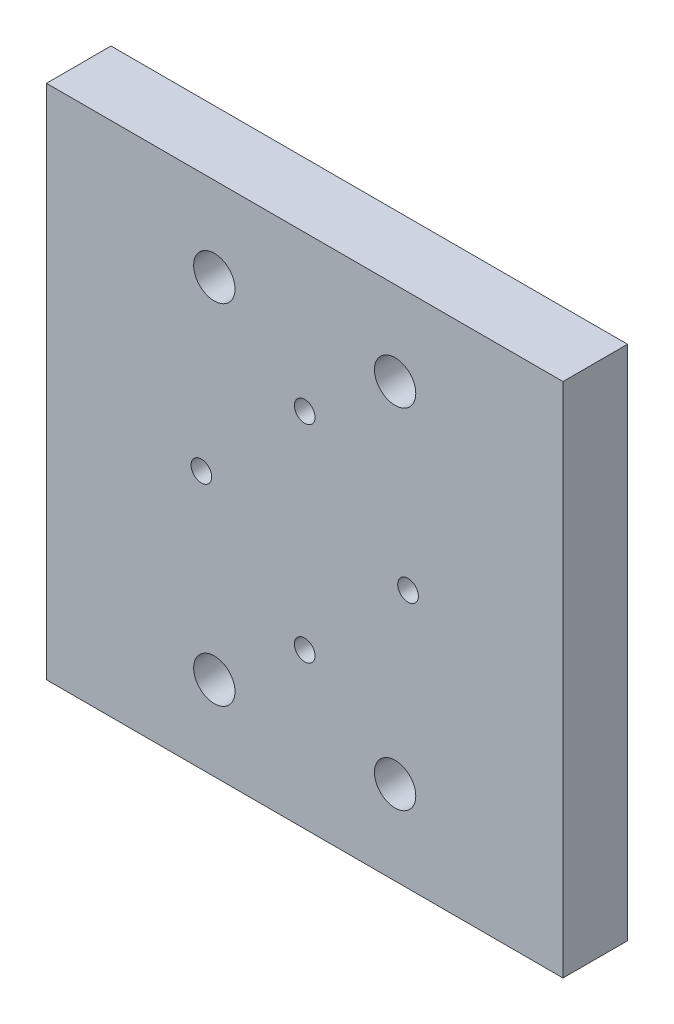
SolidWorks part; units mm, degrees
ref_plane "Front Plane" through (0, 0, 0) normal (0, 0, 1) x (1, 0, 0)
ref_plane "Top Plane" through (0, 0, 0) normal (0, 1, 0) x (1, 0, 0)
ref_plane "Right Plane" through (0, 0, 0) normal (1, 0, 0) x (0, 0, -1)
sketch "Sketch1" plane through (0, 0, 0) normal (0, 0, 1) x (1, 0, 0)
  line L1 (-20, 20) -> (20, 20)
  line L2 (-20, 20) -> (-20, -20)
  line L3 (-20, -20) -> (20, -20)
  line L4 (20, 20) -> (20, -20)
  line L5 (-20, 20) -> (20, -20) construction
  line L6 (-20, -20) -> (20, 20) construction
  circle A0 centre (0, 8) radius 0.8
  circle A1 centre (-8, 0) radius 0.8
  circle A2 centre (8, 0) radius 0.8
  circle A3 centre (0, -8) radius 0.8
  circle A4 centre (7, 13.5) radius 1.6
  circle A5 centre (-7, 13.5) radius 1.6
  circle A6 centre (7, -13.5) radius 1.6
  circle A7 centre (-7, -13.5) radius 1.6
  point P0 (0, 0)
  dimension "D2" = 8
  dimension "D3" = 8
  dimension "D4" = 8
  dimension "D1" = 8
extrude "Boss-Extrude1" add sketch "Sketch1" along normal blind 5
